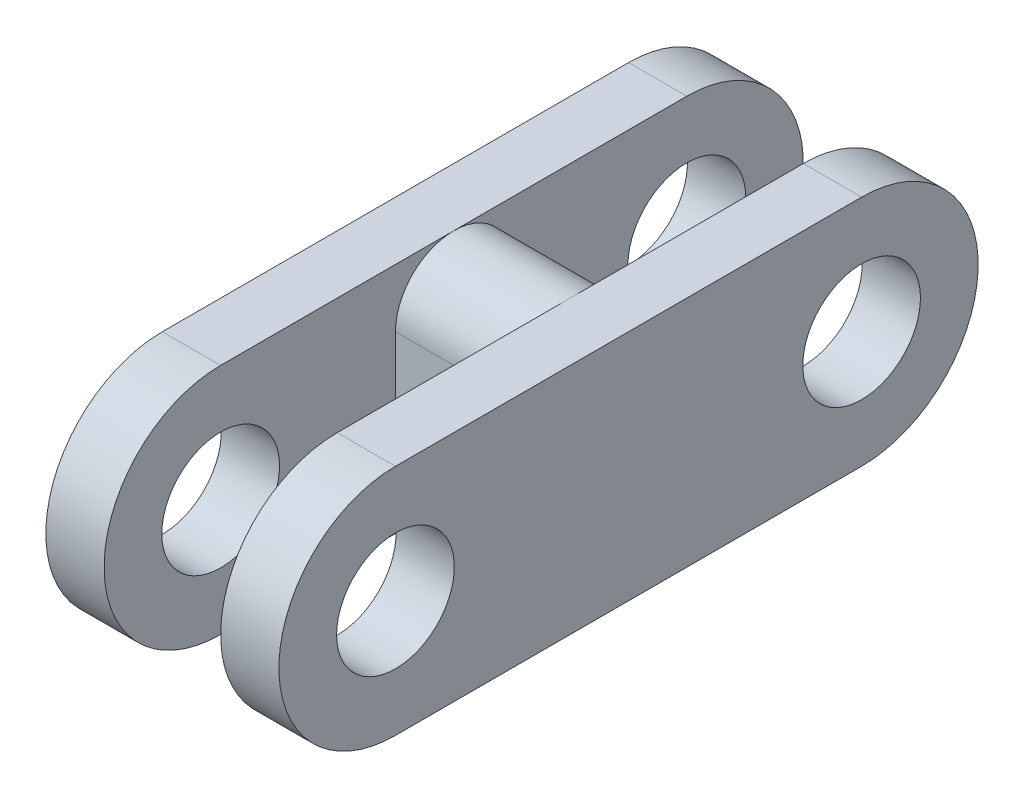
SolidWorks part; units mm, degrees
ref_plane "Front Plane" through (0, 0, 0) normal (0, 0, 1) x (1, 0, 0)
ref_plane "Top Plane" through (0, 0, 0) normal (0, 1, 0) x (1, 0, 0)
ref_plane "Right Plane" through (0, 0, 0) normal (1, 0, 0) x (0, 0, -1)
ref_plane "Plane1" through (0, 0, 0) normal (-1, 0, 0) x (0, -1, 0)
sketch "Sketch1" plane through (0, 0, 0) normal (-1, 0, 0) x (0, -1, 0)
  line L0 (10, 5) -> (10, 25)
  line L1 (0, 25) -> (0, 5)
  arc A0 (0, 5) -> (10, 5) centre (5, 5) ccw
  arc A1 (10, 25) -> (0, 25) centre (5, 25) ccw
extrude "Boss-Extrude1" add sketch "Sketch1" against normal blind 2.5
sketch "Sketch2" plane through (2.5, 0, 0) normal (1, 0, 0) x (0, 0, -1)
  line L0 (-17.5, -7.5) -> (-17.5, -2.5)
  line L1 (-12.5, -2.5) -> (-12.5, -7.5)
  arc A0 (-17.5, -2.5) -> (-12.5, -2.5) centre (-15, -2.5) cw
  arc A1 (-12.5, -7.5) -> (-17.5, -7.5) centre (-15, -7.5) cw
extrude "Boss-Extrude2" add sketch "Sketch2" along normal blind 5
sketch "Sketch3" plane through (7.5, 0, 0) normal (1, 0, 0) x (0, 0, -1)
  line L0 (-25, 0) -> (-5, 0)
  line L1 (-5, -10) -> (-25, -10)
  arc A0 (-25, -10) -> (-25, 0) centre (-25, -5) cw
  arc A1 (-5, 0) -> (-5, -10) centre (-5, -5) cw
extrude "Boss-Extrude3" add sketch "Sketch3" along normal blind 2.5
hole_wizard "Hole1" positions "Sketch5" profile "Sketch4" legacy
sketch "Sketch5" plane through (10, 0, 0) normal (1, 0, 0) x (0, 0, -1)
  point P0 (-5, -5)
sketch "Sketch4" plane through (10, -5, 5) normal (0, 1, 0) x (0, 0, -1)
  line L0 (0, 0) -> (0, 2.5)
  line L1 (0, 2.5) -> (2.525, 2.5)
  line L2 (2.525, 2.5) -> (2.525, 0)
  line L3 (2.525, 0) -> (0, 0)
  line L4 (0, 110) -> (0, -10) construction
  dimension "Diameter" = 5.05
  dimension "Depth" = 2.5
hole_wizard "Hole2" positions "Sketch7" profile "Sketch6" legacy
sketch "Sketch7" plane through (7.5, 0, 0) normal (-1, 0, 0) x (0, 0, 1)
  point P0 (25, -5)
sketch "Sketch6" plane through (7.5, -5, 25) normal (0, 1, 0) x (0, 0, 1)
  line L0 (0, 0) -> (0, 2.5)
  line L1 (0, 2.5) -> (2.525, 2.5)
  line L2 (2.525, 2.5) -> (2.525, 0)
  line L3 (2.525, 0) -> (0, 0)
  line L4 (0, 110) -> (0, -10) construction
  dimension "Diameter" = 5.05
  dimension "Depth" = 2.5
hole_wizard "Hole3" positions "Sketch9" profile "Sketch8" legacy
sketch "Sketch9" plane through (0, 0, 0) normal (-1, 0, 0) x (0, 0, 1)
  point P0 (25, -5)
  point P1 (5, -5)
sketch "Sketch8" plane through (0, -5, 25) normal (0, 1, 0) x (0, 0, 1)
  line L0 (0, 0) -> (0, 10)
  line L1 (0, 10) -> (2.525, 10)
  line L2 (2.525, 10) -> (2.525, 0)
  line L3 (2.525, 0) -> (0, 0)
  line L4 (0, 110) -> (0, -10) construction
  dimension "Diameter" = 5.05
  dimension "Depth" = 10
